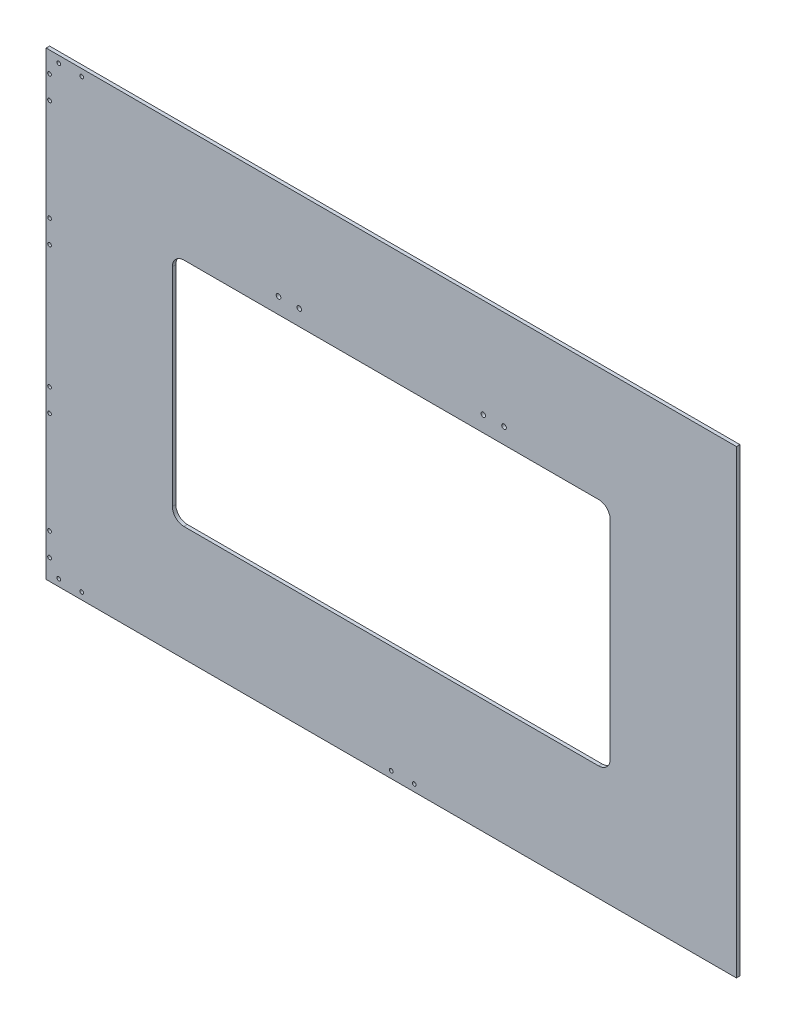
SolidWorks part; units mm, degrees
ref_plane "前视基准面" through (0, 0, 0) normal (0, 0, 1) x (1, 0, 0)
ref_plane "上视基准面" through (0, 0, 0) normal (0, 1, 0) x (1, 0, 0)
ref_plane "右视基准面" through (0, 0, 0) normal (1, 0, 0) x (0, 0, -1)
other "Configuration Table"
sketch "草图1" plane through (0, 0, 0) normal (0, 0, 1) x (1, 0, 0)
  line L1 (-300, 200) -> (300, 200)
  line L2 (-300, 200) -> (-300, -200)
  line L3 (-300, -200) -> (300, -200)
  line L4 (300, 200) -> (300, -200)
  line L5 (-300, 200) -> (300, -200) construction
  line L6 (-300, -200) -> (300, 200) construction
  point P0 (0, 0)
  dimension "D1" = 600
  dimension "D2" = 400
extrude "凸台-拉伸1" add sketch "草图1" along normal blind 3
sketch "草图2" plane through (0, 0, 3) normal (0, 0, 1) x (1, 0, 0)
  circle A0 centre (-297, 162) radius 1.6
  circle A1 centre (-297, 182) radius 1.6
  circle A2 centre (-289, 194) radius 1.6
  circle A3 centre (-269, 194) radius 1.6
  dimension "D1" = 3.2
extrude "切除-拉伸1" cut sketch "草图2" against normal through all
sketch "草图4" plane through (0, 0, 3) normal (0, 0, 1) x (1, 0, 0)
  circle A0 centre (-297, -162) radius 1.6
  circle A1 centre (-297, -182) radius 1.6
  circle A2 centre (-289, -194) radius 1.6
  circle A3 centre (-269, -194) radius 1.6
  dimension "D1" = 3.2
extrude "切除-拉伸2" cut sketch "草图4" against normal through all
sketch "草图6" plane through (0, 0, 0) normal (0, 0, -1) x (-1, 0, 0)
  circle A0 centre (0, -194) radius 1.6
  circle A1 centre (-20, -194) radius 1.6
  dimension "D1" = 3.2
extrude "切除-拉伸3" cut sketch "草图6" against normal through all
sketch "草图7" plane through (0, 0, 3) normal (0, 0, 1) x (1, 0, 0)
  line L1 (-190.25, 100.25) -> (190.25, 100.25)
  line L2 (-190.25, 100.25) -> (-190.25, -100.25)
  line L3 (-190.25, -100.25) -> (190.25, -100.25)
  line L4 (190.25, 100.25) -> (190.25, -100.25)
  line L5 (-190.25, 100.25) -> (190.25, -100.25) construction
  line L6 (-190.25, -100.25) -> (190.25, 100.25) construction
  point P0 (0, 0)
  dimension "D1" = 200.5
  dimension "D2" = 380.5
extrude "切除-拉伸4" cut sketch "草图7" against normal through all
sketch "草图8" plane through (0, 0, 3) normal (0, 0, 1) x (1, 0, 0)
  circle A0 centre (-297, 73.5) radius 1.575
  circle A1 centre (-297, 53.5) radius 1.575
  circle A2 centre (-297, -53.5) radius 1.575
  circle A3 centre (-297, -73.5) radius 1.575
  dimension "D1" = 3.15
extrude "切除-拉伸5" cut sketch "草图8" against normal through all
sketch "草图9" plane through (0, 0, 3) normal (0, 0, 1) x (1, 0, 0)
  line L0 (-98, 114) -> (-80, 114) construction
  line L2 (0, 0) -> (0, 177.0097) construction
  line L3 (98, 114) -> (80, 114) construction
  circle A0 centre (-98, 114) radius 2
  circle A1 centre (-80, 114) radius 2
  circle A2 centre (80, 114) radius 2
  circle A3 centre (98, 114) radius 2
  dimension "D1" = 4
  dimension "D2" = 114
  dimension "D3" = 80
  dimension "D4" = 18
extrude "切除-拉伸6" cut sketch "草图9" against normal through all
fillet "圆角1" radius 10 4 edges at (-190.25, -100.25, 1.5) (-190.25, 100.25, 1.5) (190.25, -100.25, 1.5) (190.25, 100.25, 1.5)
